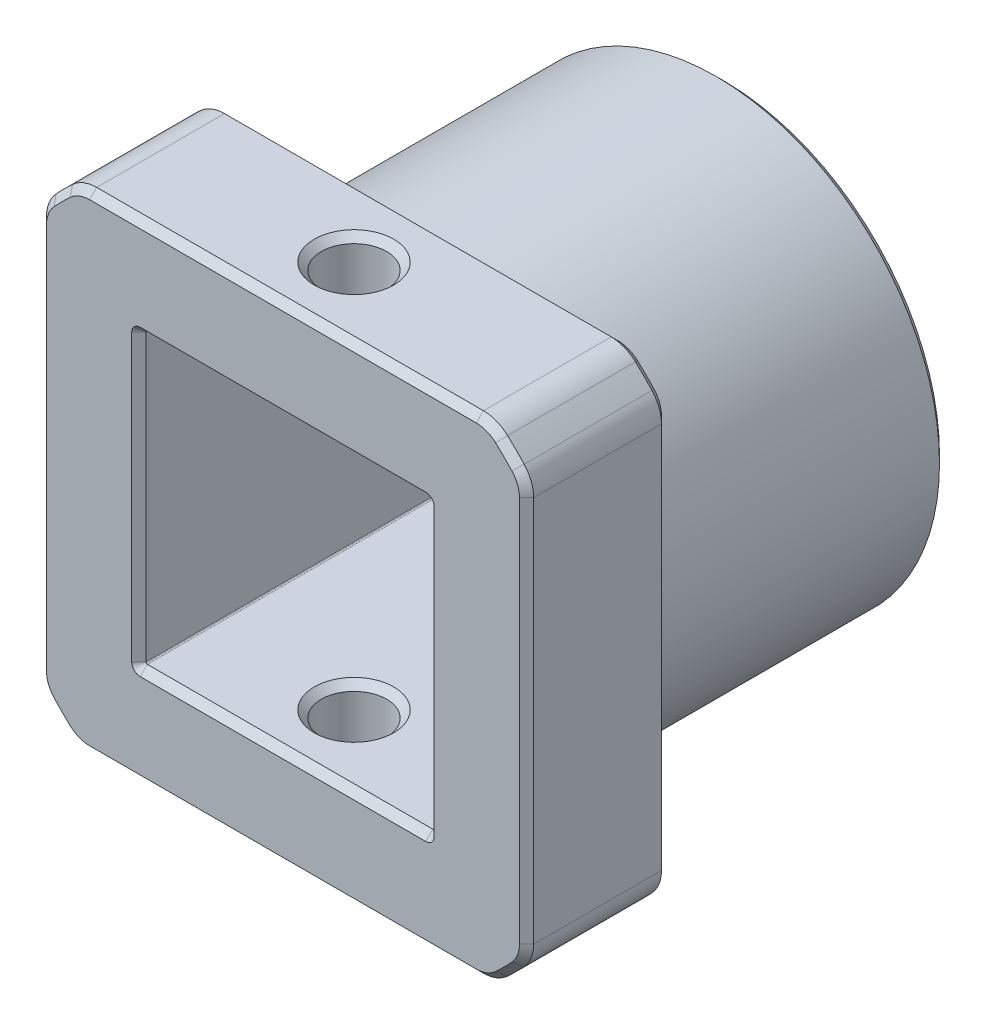
SolidWorks part; units mm, degrees
ref_plane "Front" through (0, 0, 0) normal (0, 0, 1) x (1, 0, 0)
ref_plane "Top" through (0, 0, 0) normal (0, 1, 0) x (1, 0, 0)
ref_plane "Right" through (0, 0, 0) normal (1, 0, 0) x (0, 0, -1)
sketch "Skizze1" plane through (0, 0, 0) normal (0, 0, 1) x (1, 0, 0)
  line L1 (-10.15, -10.15) -> (10.15, -10.15)
  line L2 (-10.15, -10.15) -> (-10.15, 10.15)
  line L3 (-10.15, 10.15) -> (10.15, 10.15)
  line L4 (10.15, -10.15) -> (10.15, 10.15)
  line L5 (-10.15, -10.15) -> (10.15, 10.15) construction
  line L6 (-10.15, 10.15) -> (10.15, -10.15) construction
  circle A0 centre (0, 0) radius 15.725
  point P0 (0, 0)
  dimension "D2" = 31.45
  dimension "D1" = 20.3
extrude "Aufsatz-Linear austragen1" add sketch "Skizze1" along normal blind 21
sketch "Skizze2" plane through (0, 0, 21) normal (0, 0, 1) x (1, 0, 0)
  line L0 (-14.5646, 17.15) -> (14.5646, 17.15)
  line L1 (-10.15, -10.15) -> (10.15, -10.15)
  line L2 (-10.15, -10.15) -> (-10.15, 10.15)
  line L3 (-10.15, 10.15) -> (10.15, 10.15)
  line L4 (10.15, -10.15) -> (10.15, 10.15)
  line L5 (-10.15, -10.15) -> (10.15, 10.15) construction
  line L6 (-10.15, 10.15) -> (10.15, -10.15) construction
  line L7 (0, 0) -> (13.8508, 0) construction
  line L8 (0, 0) -> (0, 13.2524) construction
  line L9 (17.15, -14.5646) -> (17.15, 14.5646)
  line L10 (14.5646, -17.15) -> (-14.5646, -17.15)
  line L11 (-17.15, 14.5646) -> (-17.15, -14.5646)
  arc A0 (-14.5646, 17.15) -> (-17.15, 14.5646) centre (0, 0) ccw
  arc A2 (-17.15, -14.5646) -> (-14.5646, -17.15) centre (0, 0) ccw
  arc A3 (14.5646, -17.15) -> (17.15, -14.5646) centre (0, 0) ccw
  arc A4 (17.15, 14.5646) -> (14.5646, 17.15) centre (0, 0) ccw
  dimension "D1" = 45
  dimension "D2" = 7
extrude "Aufsatz-Linear austragen2" add sketch "Skizze2" along normal blind 10
sketch "Skizze3" plane through (0, 17.15, 0) normal (0, 1, 0) x (1, 0, 0)
  line L0 (0, -21) -> (0, -31) construction
  line L2 (14.5646, -31) -> (-14.5646, -31) construction
  circle A0 centre (0, -26) radius 2.3
  dimension "D1" = 4.6
  dimension "D2" = 10
extrude "Schnitt-Linear austragen1" cut sketch "Skizze3" against normal through all
pattern_circular "Kreismuster1" [suppressed] count 2 over 90
fillet "Verrundung1" radius 0.1 4 edges at (10.15, -10.15, 15.5) (-10.15, -10.15, 15.5) (-10.15, 10.15, 15.5) (10.15, 10.15, 15.5)
fillet "Verrundung2" radius 2.5 8 edges at (-17.15, -14.5646, 26) (-14.5646, -17.15, 26) (14.5646, -17.15, 26) (17.15, -14.5646, 26) (17.15, 14.5646, 26) (14.5646, 17.15, 26) (-17.15, 14.5646, 26) (-14.5646, 17.15, 26)
chamfer "Fase1" distance 0.5 angle 45 37 edges at (-10.1207, -10.1207, 0) (-10.15, 0, 0) (-10.1207, 10.1207, 0) (0, 10.15, 0) (10.1207, 10.1207, 0) (10.15, 0, 0) (10.1207, -10.1207, 0) (0, -10.15, 0) (15.725, 0, 0) (-10.1207, 10.1207, 31) (-10.15, 0, 31) (-10.1207, -10.1207, 31) (0, -10.15, 31) (10.1207, -10.1207, 31) (10.15, 0, 31) (10.1207, 10.1207, 31) (0, 10.15, 31) (-16.9768, 14.5296, 31) (-15.9099, 15.9099, 31) (-14.5296, 16.9768, 31) (0, 17.15, 31) (14.5296, 16.9768, 31) (15.9099, 15.9099, 31) (16.9768, 14.5296, 31) (17.15, 0, 31) (16.9768, -14.5296, 31) (15.9099, -15.9099, 31) (14.5296, -16.9768, 31) (0, -17.15, 31) (-14.5296, -16.9768, 31) (-15.9099, -15.9099, 31) (-16.9768, -14.5296, 31) (-17.15, 0, 31) (0, -10.15, 28.3) (0, 10.15, 23.7) (0, -17.15, 28.3) (0, 17.15, 28.3)
chamfer "Fase2" [suppressed] distance 0.3 angle 45
chamfer "Fase3" [suppressed] distance 0.5 angle 45
chamfer "Fase4" distance 0.5 angle 45 16 edges at (0, -17.15, 21) (14.5296, -16.9768, 21) (-14.5296, -16.9768, 21) (15.9099, -15.9099, 21) (-15.9099, -15.9099, 21) (16.9768, -14.5296, 21) (-16.9768, -14.5296, 21) (17.15, 0, 21) (-17.15, 0, 21) (16.9768, 14.5296, 21) (-16.9768, 14.5296, 21) (15.9099, 15.9099, 21) (-15.9099, 15.9099, 21) (14.5296, 16.9768, 21) (-14.5296, 16.9768, 21) (0, 17.15, 21)
